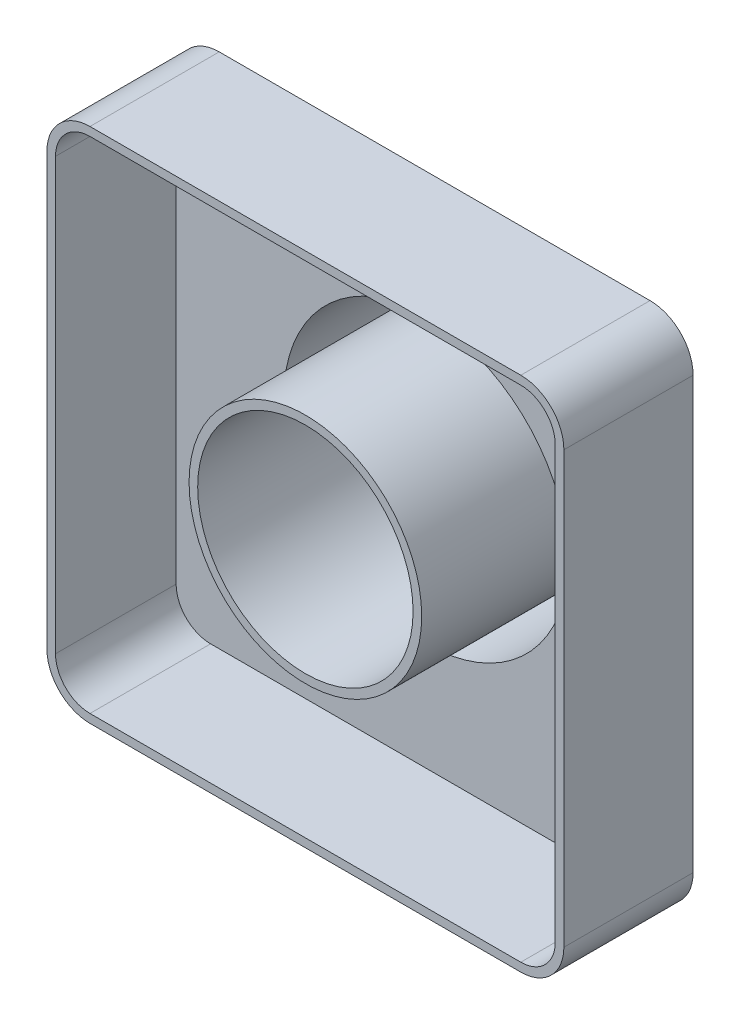
SolidWorks part; units mm, degrees
ref_plane "Front Plane" through (0, 0, 0) normal (0, 0, 1) x (1, 0, 0)
ref_plane "Top Plane" through (0, 0, 0) normal (0, 1, 0) x (1, 0, 0)
ref_plane "Right Plane" through (0, 0, 0) normal (1, 0, 0) x (0, 0, -1)
sketch "Sketch1" plane through (0, 0, 0) normal (0, 0, 1) x (1, 0, 0)
  line L1 (0, 0) -> (120, 0)
  line L2 (0, 0) -> (0, 120)
  line L3 (0, 120) -> (120, 120)
  line L4 (120, 0) -> (120, 120)
  dimension "D1" = 120
  dimension "D2" = 120
sketch "Sketch4" plane through (0, 0, 0) normal (0, 0, 1) x (1, 0, 0)
extrude "Boss-Extrude3" add sketch "Sketch1" along normal blind 30
sketch "Sketch5" plane through (0, 0, 0) normal (0, 0, 1) x (1, 0, 0)
  circle A0 centre (60, 60) radius 35
  dimension "D1" = 70
extrude "Boss-Extrude5" add sketch "Sketch5" against normal blind 25 contours A0
sketch "Sketch7" plane through (0, 0, 0) normal (0, 0, 1) x (1, 0, 0)
  circle A0 centre (60, 60) radius 25
  dimension "D1" = 50
extrude "Cut-Extrude3" cut sketch "Sketch7" along normal blind 75 and the other way blind 67 contours A0
fillet "Fillet3" radius 10 4 edges at (120, 120, 15) (0, 120, 15) (120, 0, 15) (0, 0, 15)
shell "Shell1" thickness 2
